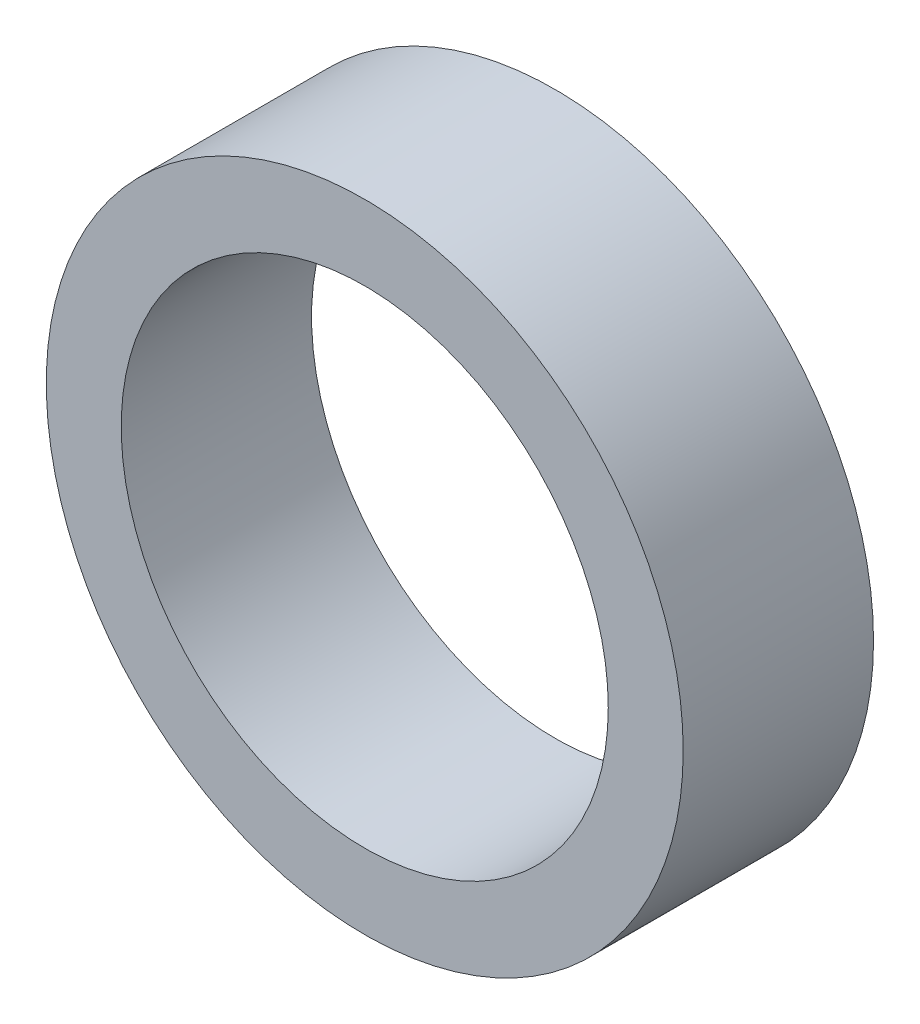
SolidWorks part; units mm, degrees
ref_plane "Front Plane" through (0, 0, 0) normal (0, 0, 1) x (1, 0, 0)
ref_plane "Top Plane" through (0, 0, 0) normal (0, 1, 0) x (1, 0, 0)
ref_plane "Right Plane" through (0, 0, 0) normal (1, 0, 0) x (0, 0, -1)
sketch "Sketch1" plane through (0, 0, 0) normal (0, 0, 1) x (1, 0, 0)
  circle A0 centre (0, 0) radius 3.25
  circle A1 centre (0, 0) radius 4.25
  dimension "D1" = 6.5
  dimension "D2" = 8.5
extrude "Boss-Extrude1" add sketch "Sketch1" along normal blind 2.54
